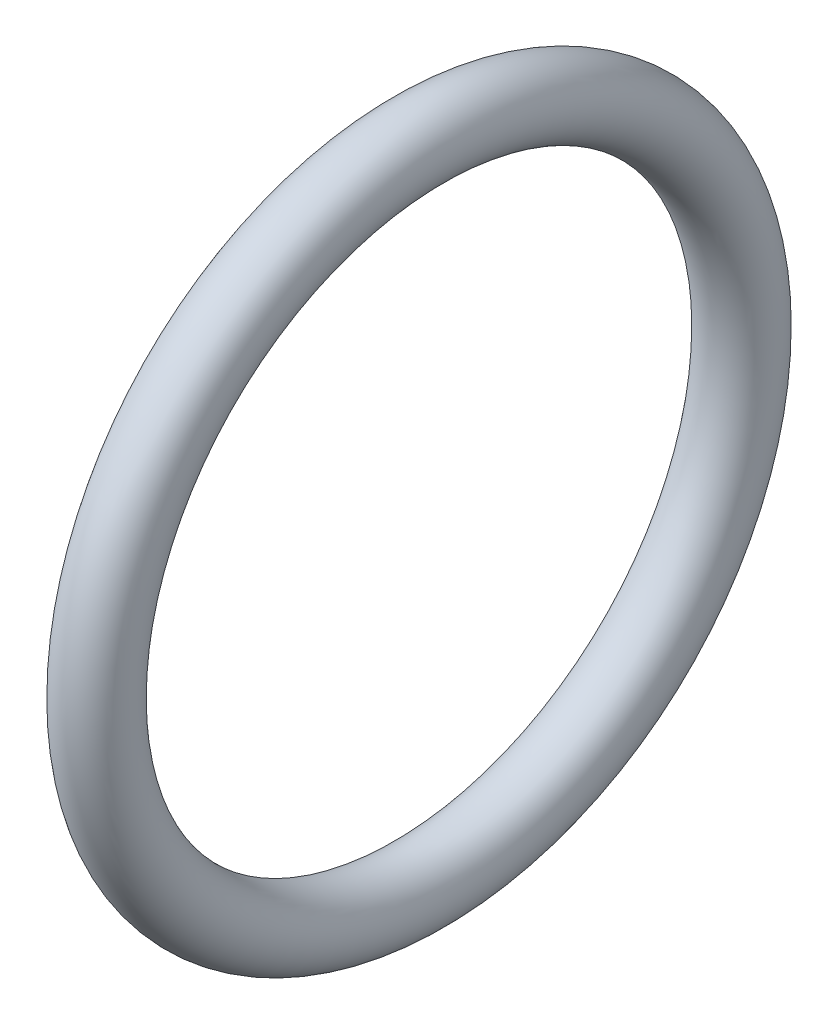
SolidWorks part; units mm, degrees
ref_plane "Front Plane" through (0, 0, 0) normal (0, 0, 1) x (1, 0, 0)
ref_plane "Top Plane" through (0, 0, 0) normal (0, 1, 0) x (1, 0, 0)
ref_plane "Right Plane" through (0, 0, 0) normal (1, 0, 0) x (0, 0, -1)
sketch "Sketch1" plane through (0, 0, 0) normal (0, 0, 1) x (1, 0, 0)
  line L0 (-1.5, 13.75) -> (-1.5, 0)
  line L1 (1.5, 13.75) -> (1.5, 0)
  line L2 (-1.5, 0) -> (1.5, 0) construction
  circle A0 centre (0, 13.75) radius 1.5
  dimension "D1" = 3
  dimension "D2" = 12.25
revolve "Revolve1" add sketch "Sketch1" angle 360 about L2
